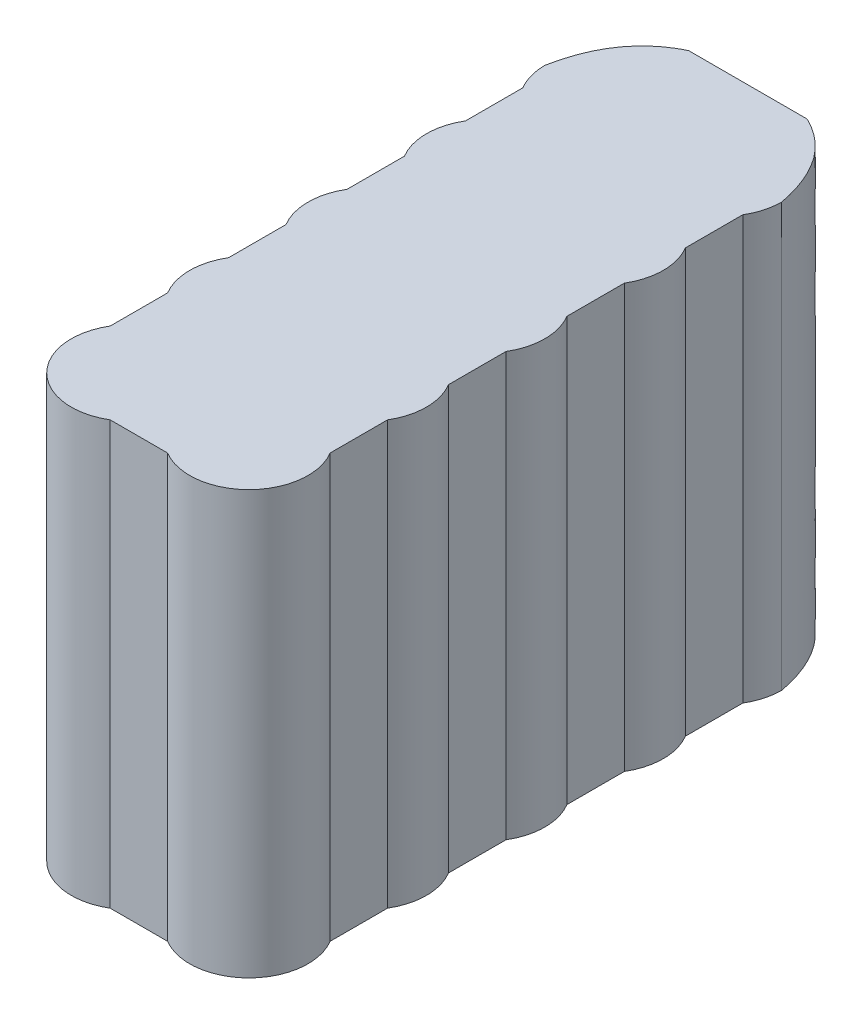
SolidWorks part; units mm, degrees
ref_plane "Front Plane" through (0, 0, 0) normal (0, 0, 1) x (1, 0, 0)
ref_plane "Top Plane" through (0, 0, 0) normal (0, 1, 0) x (1, 0, 0)
ref_plane "Right Plane" through (0, 0, 0) normal (1, 0, 0) x (0, 0, -1)
sketch "Sketch1" plane through (0, 0, 0) normal (0, 1, 0) x (1, 0, 0)
  line L0 (0, 35) -> (0, -35) construction
  line L1 (-14, -35) -> (14, -35)
  line L2 (-14, -35) -> (-14, 35)
  line L3 (-14, 35) -> (14, 35)
  line L4 (14, -35) -> (14, 35)
  line L5 (-14, -35) -> (14, 35) construction
  line L6 (-14, 35) -> (14, -35) construction
  line L7 (0, 0) -> (14, 0) construction
  line L8 (14, 0) -> (7, 0) construction
  line L9 (7, 0) -> (7, 35) construction
  line L10 (7, 28) -> (7, 14) construction
  line L11 (-13, 35) -> (-13, -35)
  line L12 (-7, 35) -> (7, 35)
  line L13 (-7, 35) -> (-7, 38)
  line L14 (-7, 38) -> (7, 38)
  line L15 (7, 35) -> (7, 38)
  line L16 (-14, -34) -> (14, -34)
  line L17 (13, 35) -> (13, -35)
  line L18 (-14, 34) -> (14, 34)
  circle A0 centre (7, 28) radius 7
  circle A1 centre (-7, 28) radius 7
  circle A2 centre (-7, 14) radius 7
  circle A3 centre (-7, 0) radius 7
  circle A4 centre (-7, -14) radius 7
  circle A5 centre (-7, -28) radius 7
  circle A6 centre (7, 14) radius 7
  circle A7 centre (7, 0) radius 7
  circle A8 centre (7, -14) radius 7
  circle A9 centre (7, -28) radius 7
  point P0 (0, 0)
  dimension "D3" = 7
  dimension "D4" = 14
  dimension "D1" = 28
  dimension "D2" = 70
  dimension "D6" = 14
  dimension "D7" = 3
  dimension "D8" = 1
  dimension "D9" = 1
  dimension "D5" = 5
sketch "Sketch2" plane through (0, 0, 0) normal (0, 1, 0) x (1, 0, 0)
  line L12 (7, 38) -> (-7, 38)
  line L13 (7, 35) -> (7, 38)
  line L14 (-7, 35) -> (7, 35)
  line L15 (-7, 38) -> (-7, 35)
  line L16 (7, 38) -> (-7, 38)
  line L24 (-13, 24.3944) -> (-13, 17.6056)
  line L27 (13, 24.3944) -> (13, 17.6056)
  line L28 (-13, 10.3944) -> (-13, 3.6056)
  line L29 (-13, -3.6056) -> (-13, -10.3944)
  line L31 (-13, -17.6056) -> (-13, -24.3944)
  line L32 (-3.3944, -34) -> (3.3944, -34)
  line L35 (13, -17.6056) -> (13, -24.3944)
  line L36 (13, -3.6056) -> (13, -10.3944)
  line L37 (13, 10.3944) -> (13, 3.6056)
  circle A1 centre (7, 28) radius 7
  arc A2 (13, 24.3944) -> (12.8199, 31.8896) centre (7, 28) ccw
  circle A3 centre (7, -14) radius 7
  arc A4 (13, -17.6056) -> (13, -10.3944) centre (7, -14) ccw
  circle A5 centre (7, 0) radius 7
  arc A6 (13, -3.6056) -> (13, 3.6056) centre (7, 0) ccw
  circle A7 centre (7, 14) radius 7
  arc A8 (13, 10.3944) -> (13, 17.6056) centre (7, 14) ccw
  circle A9 centre (-7, -28) radius 7
  arc A10 (-13, -24.3944) -> (-3.3944, -34) centre (-7, -28) ccw
  circle A11 centre (-7, -14) radius 7
  arc A12 (-13, -10.3944) -> (-13, -17.6056) centre (-7, -14) ccw
  circle A13 centre (-7, 0) radius 7
  arc A14 (-13, 3.6056) -> (-13, -3.6056) centre (-7, 0) ccw
  circle A15 centre (-7, 14) radius 7
  arc A16 (-13, 17.6056) -> (-13, 10.3944) centre (-7, 14) ccw
  circle A17 centre (-7, 28) radius 7
  arc A18 (-12.8199, 31.8896) -> (-13, 24.3944) centre (-7, 28) ccw
  circle A19 centre (7, -28) radius 7
  arc A20 (3.3944, -34) -> (13, -24.3944) centre (7, -28) ccw
  spline S0 degree 2 poles (-14, 28) (-12.5964, 35.3289) (-7, 38) knots 0 0 0 0.317771 0.317771 0.317771
  spline S1 degree 2 poles (7, 38) (12.5964, 35.3289) (14, 28) knots 0.682229 0.682229 0.682229 1 1 1
  dimension "D1" = 0
  dimension "D3" = 0
  dimension "D4" = 0
  dimension "D5" = 0
  dimension "D6" = 0
  dimension "D7" = 0
  dimension "D8" = 0
  dimension "D9" = 0
  dimension "D10" = 0
  dimension "D11" = 0
  dimension "D12" = 0
extrude "Boss-Extrude1" add sketch "Sketch2" along normal blind 50 contours S1 L16 S0 A18 L24 A16 L28 A14 L29 A12 L31 A10 L32 A20 L35 A4 L36 A6 L37 A8 L27 A2
